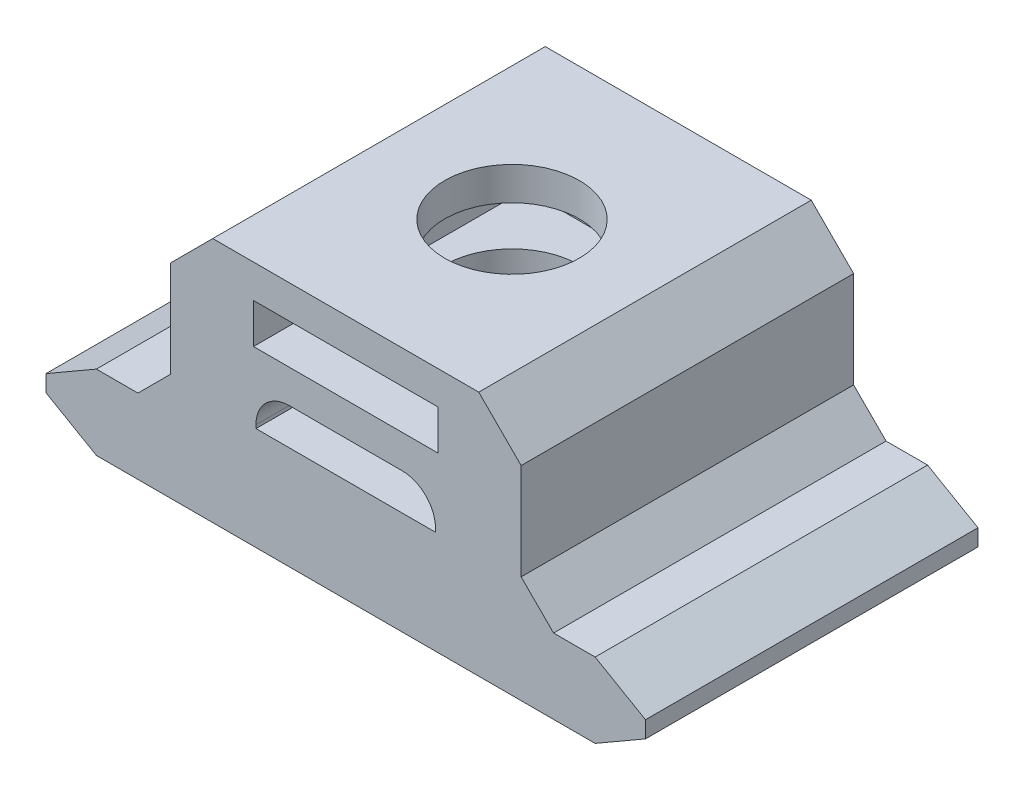
SolidWorks part; units mm, degrees
ref_plane "Front Plane" through (0, 0, 0) normal (0, 0, 1) x (1, 0, 0)
ref_plane "Top Plane" through (0, 0, 0) normal (0, 1, 0) x (1, 0, 0)
ref_plane "Right Plane" through (0, 0, 0) normal (1, 0, 0) x (0, 0, -1)
sketch "Sketch1" plane through (0, 0, 0) normal (0, 0, 1) x (1, 0, 0)
  line L0 (0, 20.74) -> (0, 0) construction
  line L1 (5.55, 8.8) -> (-5.55, 8.8)
  line L2 (-5.55, 8.8) -> (-5.55, 11.2)
  line L3 (-5.55, 11.2) -> (5.55, 11.2)
  line L4 (-10.5, 0) -> (-3.5, 0)
  line L5 (-10.5, 0) -> (-10.5, 1.7)
  line L6 (-10.5, 1.7) -> (-5.4, 1.7)
  line L7 (-5.4, 1.7) -> (-5.4, 4.8)
  line L8 (-3.4, 6.8) -> (3.4, 6.8)
  line L9 (-3.5, -1.6) -> (-15, -1.6)
  line L11 (-8, 13.2) -> (-10.55, 10.65)
  line L12 (-8, 13.2) -> (8, 13.2)
  line L13 (-3.5, 0) -> (-3.5, -1.6)
  line L14 (-10.55, 10.65) -> (-10.55, 4.85)
  line L15 (-10.55, 4.85) -> (-12.5, 2.9)
  line L16 (-12.5, 2.9) -> (-15, 2.9)
  line L17 (12.5, 2.9) -> (15, 2.9)
  line L18 (10.55, 4.85) -> (12.5, 2.9)
  line L19 (10.55, 10.65) -> (10.55, 4.85)
  line L20 (3.5, 0) -> (3.5, -1.6)
  line L21 (8, 13.2) -> (10.55, 10.65)
  line L23 (3.5, -1.6) -> (15, -1.6)
  line L24 (5.4, 1.7) -> (5.4, 4.8)
  line L25 (10.5, 1.7) -> (5.4, 1.7)
  line L26 (10.5, 0) -> (10.5, 1.7)
  line L27 (10.5, 0) -> (3.5, 0)
  line L28 (5.55, 8.8) -> (5.55, 11.2)
  line L29 (-15, -1.6) -> (-18.0311, 0.15)
  line L30 (-18.0311, 0.15) -> (-18.0311, 1.15)
  line L31 (-18.0311, 1.15) -> (-15, 2.9)
  line L32 (-18.0311, 0.65) -> (-14.6187, 0.65) construction
  line L33 (15, -1.6) -> (18.0311, 0.15)
  line L34 (18.0311, 0.15) -> (18.0311, 1.15)
  line L35 (18.0311, 1.15) -> (15, 2.9)
  arc A1 (-3.4, 6.8) -> (-5.4, 4.8) centre (-3.4, 4.8) ccw
  arc A2 (3.4, 6.8) -> (5.4, 4.8) centre (3.4, 4.8) cw
  point P18 (0, 6.8)
  point P42 (0, 13.2)
  point P43 (0, 6.8)
  point P47 (0, 11.2)
  point P48 (0, 8.8)
  dimension "D14" = 120
  dimension "D18" = 2
  dimension "D1" = 7
  dimension "D2" = 10.5
  dimension "D3" = 6.8
  dimension "D4" = 10.8
  dimension "D5" = 1.6
  dimension "D6" = 2.4
  dimension "D7" = 11.1
  dimension "D8" = 2
  dimension "D9" = 2
  dimension "D10" = 8
  dimension "D11" = 135
  dimension "D12" = 5
  dimension "D13" = 1.7
  dimension "D15" = 4.5
  dimension "D16" = 120
  dimension "D17" = 2.5
  dimension "D19" = 1
  dimension "D20" = 30
extrude "Boss-Extrude1" add sketch "Sketch1" along normal blind 20
sketch "Sketch2" plane through (0, 13.2, 0) normal (0, 1, 0) x (1, 0, 0)
  line L0 (0, -10) -> (0, 0) construction
  line L1 (0, -10) -> (8, -10) construction
  line L2 (8, -20) -> (8, 0) construction
  circle A0 centre (0, -10) radius 4.05
  point P2 (8, -10)
  dimension "D1" = 8.1
extrude "Cut-Extrude1" cut sketch "Sketch2" against normal up to surface (13.2 mm away) up to face at (7, 0, 10)
sketch "Sketch4" plane through (0, 13.2, 0) normal (0, 1, 0) x (1, 0, 0)
  line L0 (8, 0) -> (-8, 0) construction
  line L1 (-5.55, 0) -> (5.55, 0)
  line L2 (-5.55, 0) -> (-5.55, -3.65)
  line L3 (-5.55, -3.65) -> (5.55, -3.65)
  line L4 (5.55, 0) -> (5.55, -3.65)
  line L5 (5.55, -20) -> (5.55, 0) construction
  line L6 (-5.55, -20) -> (-5.55, 0) construction
  circle A0 centre (0, -10) radius 4.05 construction
  dimension "D1" = 6.35
extrude "Boss-Extrude3" add sketch "Sketch4" against normal up to surface (4.4 mm away) up to face at (0, 8.8, 14.05)
sketch "Sketch5" plane through (0, 0, 0) normal (0, 0, -1) x (-1, 0, 0)
  line L0 (-10.5, 1.7) -> (-10.5, -1.6)
  line L1 (-3.5, -1.6) -> (-15, -1.6) construction
  line L2 (-10.5, -1.6) -> (10.5, -1.6)
  line L3 (15, -1.6) -> (3.5, -1.6) construction
  line L4 (10.5, -1.6) -> (10.5, 1.7)
  line L5 (10.5, 1.7) -> (5.4, 1.7)
  line L6 (5.4, 1.7) -> (5.4, 4.6)
  line L7 (5.4, 4.6) -> (-5.4, 4.6)
  line L8 (-5.4, 4.6) -> (-5.4, 1.7)
  line L9 (-5.4, 1.7) -> (-10.5, 1.7) construction
  line L10 (-5.4, 1.7) -> (-10.5, 1.7)
  line L11 (-5.4, 4.8) -> (-5.4, 1.7) construction
  line L12 (5.4, 1.7) -> (5.4, 4.8) construction
  line L13 (10.5, 1.7) -> (5.4, 1.7) construction
  line L14 (10.5, 0) -> (10.5, 1.7) construction
  dimension "D1" = 2.9
extrude "Boss-Extrude4" add sketch "Sketch5" against normal blind 1.9
sketch "Sketch6" plane through (0, 0, 20) normal (0, 0, 1) x (1, 0, 0)
  line L0 (-3.5, -1.6) -> (-3.5, 0)
  line L1 (-3.5, 0) -> (-10.5, 0)
  line L2 (-10.5, 0) -> (-10.5, 1.7)
  line L3 (-10.5, 1.7) -> (-5.4, 1.7)
  line L4 (-5.4, 1.7) -> (-5.4, 4.6)
  line L5 (-5.4, 4.6) -> (5.4, 4.6)
  line L6 (5.4, 4.6) -> (5.4, 1.7)
  line L7 (5.4, 1.7) -> (10.5, 1.7) construction
  line L8 (5.4, 4.8) -> (5.4, 1.7) construction
  line L9 (5.4, 1.7) -> (10.5, 1.7)
  line L10 (10.5, 1.7) -> (10.5, 0)
  line L11 (10.5, 0) -> (3.5, 0)
  line L12 (3.5, 0) -> (3.5, -1.6)
  line L13 (3.5, -1.6) -> (-3.5, -1.6)
extrude "Boss-Extrude5" add sketch "Sketch6" against normal blind 5.9
